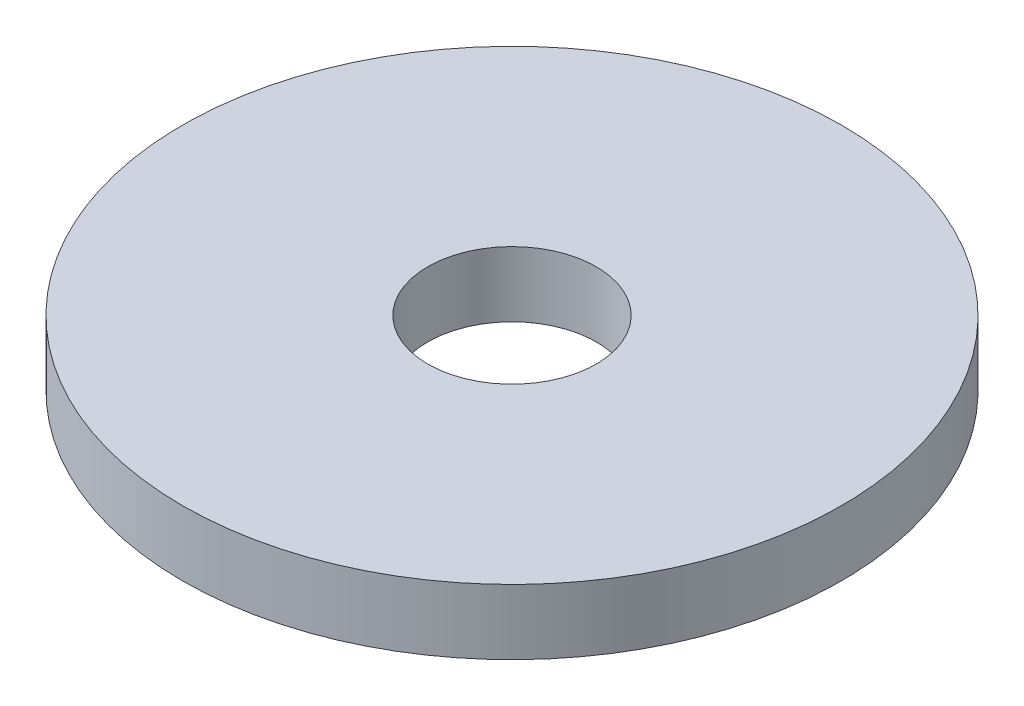
SolidWorks part; units mm, degrees
ref_plane "前视基准面" through (0, 0, 0) normal (0, 0, 1) x (1, 0, 0)
ref_plane "上视基准面" through (0, 0, 0) normal (0, 1, 0) x (1, 0, 0)
ref_plane "右视基准面" through (0, 0, 0) normal (1, 0, 0) x (0, 0, -1)
sketch "草图1" plane through (0, 0, 0) normal (0, 1, 0) x (1, 0, 0)
  circle A0 centre (0, 0) radius 43
  circle A1 centre (0, 0) radius 11
  dimension "D1" = 86
  dimension "D2" = 22
extrude "凸台-拉伸1" add sketch "草图1" along normal blind 8.5
